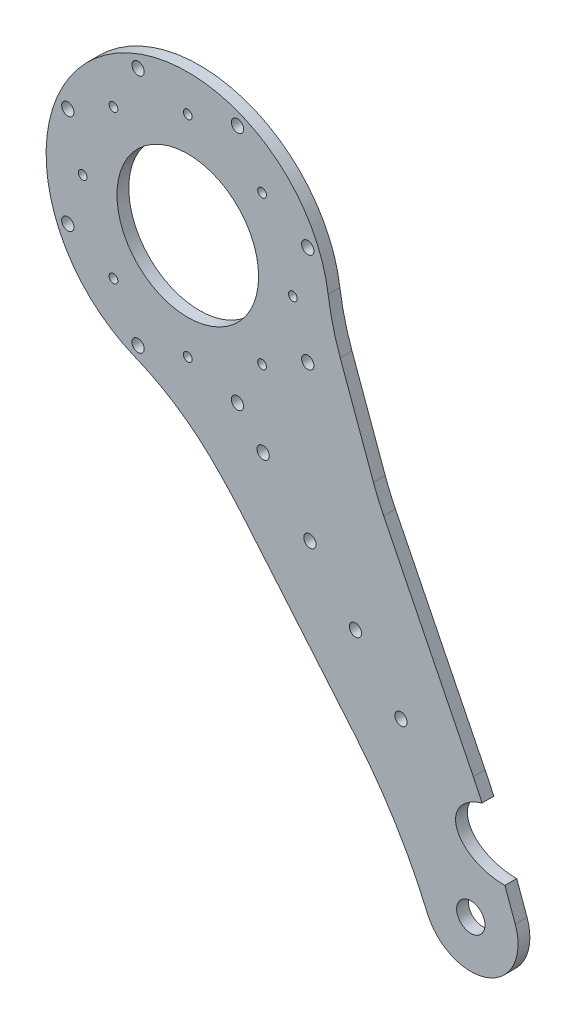
SolidWorks part; units mm, degrees
ref_plane "前视基准面" through (0, 0, 0) normal (0, 0, 1) x (1, 0, 0)
ref_plane "上视基准面" through (0, 0, 0) normal (0, 1, 0) x (1, 0, 0)
ref_plane "右视基准面" through (0, 0, 0) normal (1, 0, 0) x (0, 0, -1)
other "Configuration Table"
sketch "草图1" plane through (0, 0, 0) normal (0, 0, 1) x (1, 0, 0)
  line L0 (60, 0) -> (80.5212, -56.3816)
  line L1 (60, 0) -> (0, 0) construction
  line L2 (0, 0) -> (-56.3816, -20.5212) construction
  line L3 (-56.3816, -20.5212) -> (12.5624, -78.3721)
  line L4 (12.5624, -78.3721) -> (80.5212, -56.3816)
  line L5 (80.5212, -56.3816) -> (113.0212, -112.6732)
  line L6 (12.5624, -78.3721) -> (92.7533, -173.9399)
  line L7 (113.0212, -112.6732) -> (138.6727, -183.1502)
  line L8 (101.085, -196.831) -> (138.6727, -183.1502) construction
  line L9 (101.085, -196.831) -> (92.7533, -173.9399)
  line L10 (125.847, -147.9117) -> (80.5212, -56.3816)
  circle A0 centre (0, 0) radius 30
  circle A1 centre (0, 0) radius 60
  circle A2 centre (119.8789, -189.9906) radius 6
  circle A3 centre (119.8789, -189.9906) radius 20
  dimension "D1" = 60
  dimension "D2" = 120
  dimension "D9" = 65
  dimension "D11" = 12
  dimension "D12" = 40
  dimension "D3" = 160
  dimension "D4" = 110
  dimension "D5" = 60
  dimension "D6" = 60
  dimension "D7" = 90
  dimension "D8" = 170
  dimension "D10" = 190
  dimension "D13" = 170
  dimension "D15" = 75
  dimension "D16" = 90
extrude "凸台-拉伸1" add sketch "草图1" along normal blind 5 contours A1 L3 A0 | A1 L3 L4 L0 | A3 L7 L5 L4 L6 L9 | A3 A2
sketch "草图2" plane through (0, 0, 5) normal (0, 0, 1) x (1, 0, 0)
  line L0 (0, 60) -> (0, 0) construction
  line L1 (-60, 0) -> (60, 0) construction
  line L6 (-10.4189, -59.0885) -> (12.5624, -78.3721)
  line L7 (12.5624, -78.3721) -> (92.7533, -173.9399)
  line L8 (92.7533, -173.9399) -> (101.085, -196.831)
  line L9 (138.6727, -183.1502) -> (125.847, -147.9117)
  line L10 (125.847, -147.9117) -> (80.5212, -56.3816)
  line L11 (80.5212, -56.3816) -> (60, 0)
  line L12 (-10.4189, -59.0885) -> (12.5624, -78.3721)
  line L13 (12.5624, -78.3721) -> (92.7533, -173.9399)
  line L14 (92.7533, -173.9399) -> (101.085, -196.831)
  line L15 (138.6727, -183.1502) -> (125.847, -147.9117)
  line L16 (125.847, -147.9117) -> (80.5212, -56.3816)
  line L17 (80.5212, -56.3816) -> (60, 0)
  circle A0 centre (0, 44.5) radius 1.85
  circle A1 centre (31.4663, 31.4663) radius 1.85
  arc A2 (60, 0) -> (-10.4189, -59.0885) centre (0, 0) ccw
  arc A3 (101.085, -196.831) -> (138.6727, -183.1502) centre (119.8789, -189.9906) ccw
  arc A4 (60, 0) -> (-10.4189, -59.0885) centre (0, 0) ccw
  arc A5 (101.085, -196.831) -> (138.6727, -183.1502) centre (119.8789, -189.9906) ccw
  circle A6 centre (44.5, 0) radius 1.85
  circle A7 centre (31.4663, -31.4663) radius 1.85
  circle A8 centre (0, -44.5) radius 1.85
  circle A9 centre (-31.4663, -31.4663) radius 1.85
  circle A10 centre (-44.5, 0) radius 1.85
  circle A11 centre (-31.4663, 31.4663) radius 1.85
  circle A12 centre (42.5, 0) radius 1.6
  circle A13 centre (-42.5, 0) radius 1.85
  point P30 (0, 0)
  dimension "D2" = 3.7
  dimension "D3" = 44.5
  dimension "D5" = 3.7
  dimension "D6" = 3.2
  dimension "D7" = 42.5
  dimension "D8" = 42.5
  dimension "D1" = 0
  dimension "D4" = 8
extrude "切除-拉伸1" cut sketch "草图2" against normal blind 10 contours A0 | A1 | A6 A12 | A6 A12 | A7 | A8 | A10 A13 | A10 A13 | A11 | A9
sketch "草图3" plane through (0, 0, 5) normal (0, 0, 1) x (1, 0, 0)
  line L0 (0, 0) -> (0, 60) construction
  line L1 (0, 0) -> (31.4663, 31.4663) construction
  line L2 (0, 0) -> (22.961, 55.4328) construction
  line L6 (-10.4189, -59.0885) -> (12.5624, -78.3721)
  line L7 (12.5624, -78.3721) -> (92.7533, -173.9399)
  line L8 (92.7533, -173.9399) -> (101.085, -196.831)
  line L9 (138.6727, -183.1502) -> (125.847, -147.9117)
  line L10 (125.847, -147.9117) -> (80.5212, -56.3816)
  line L11 (80.5212, -56.3816) -> (60, 0)
  line L12 (-10.4189, -59.0885) -> (12.5624, -78.3721)
  line L13 (12.5624, -78.3721) -> (92.7533, -173.9399)
  line L14 (92.7533, -173.9399) -> (101.085, -196.831)
  line L15 (138.6727, -183.1502) -> (125.847, -147.9117)
  line L16 (125.847, -147.9117) -> (80.5212, -56.3816)
  line L17 (80.5212, -56.3816) -> (60, 0)
  circle A0 centre (21.0476, 50.8134) radius 2.6
  circle A1 centre (50.8134, 21.0476) radius 2.6
  arc A2 (60, 0) -> (-10.4189, -59.0885) centre (0, 0) ccw
  arc A3 (101.085, -196.831) -> (138.6727, -183.1502) centre (119.8789, -189.9906) ccw
  arc A4 (60, 0) -> (-10.4189, -59.0885) centre (0, 0) ccw
  arc A5 (101.085, -196.831) -> (138.6727, -183.1502) centre (119.8789, -189.9906) ccw
  circle A6 centre (50.8134, -21.0476) radius 2.6
  circle A7 centre (21.0476, -50.8134) radius 2.6
  circle A8 centre (-21.0476, -50.8134) radius 2.6
  circle A9 centre (-50.8134, -21.0476) radius 2.6
  circle A10 centre (-50.8134, 21.0476) radius 2.6
  circle A11 centre (-21.0476, 50.8134) radius 2.6
  point P33 (0, 0)
  dimension "D3" = 5.2
  dimension "D4" = 55
  dimension "D2" = 22.5
  dimension "D1" = 0
  dimension "D5" = 8
extrude "切除-拉伸2" cut sketch "草图3" against normal blind 10 contours A10 | A9 | A8 | A7 | A6 | A1 | A0 | A11
fillet "圆角1" radius 200 1 edges at (125.847, -147.9117, 2.5)
fillet "圆角2" radius 200 1 edges at (92.7533, -173.9399, 2.5)
fillet "圆角3" radius 200 1 edges at (12.5624, -78.3721, 2.5)
fillet "圆角5" radius 100 3 edges at (80.5212, -56.3816, 2.5) (60, 0, 2.5) (-10.4189, -59.0885, 2.5)
sketch "草图4" plane through (0, 0, 5) normal (0, 0, 1) x (1, 0, 0)
  line L5 (138.6727, -183.1502) -> (129.6382, -158.328)
  line L6 (120.9279, -137.9781) -> (82.9808, -61.3483)
  line L7 (78.6256, -51.1734) -> (64.5536, -12.5109)
  line L8 (23.8098, -91.7761) -> (70.6774, -147.6308)
  line L9 (42.9609, -75.7064) -> (89.8285, -131.5612)
  line L10 (138.6727, -183.1502) -> (129.6382, -158.328)
  line L11 (120.9279, -137.9781) -> (82.9808, -61.3483)
  line L12 (78.6256, -51.1734) -> (64.5536, -12.5109)
  line L13 (23.8098, -91.7761) -> (70.6774, -147.6308)
  line L15 (89.8877, -131.6317) -> (89.8877, -131.6317)
  line L16 (89.8877, -131.6317) -> (60.5772, -72.4426)
  line L17 (55.1333, -59.7239) -> (41.0613, -21.0614)
  circle A0 centre (31.9151, -63.6228) radius 2.6
  circle A1 centre (51.7254, -86.1517) radius 2.6
  circle A2 centre (63.0234, -24.2033) radius 2.6
  circle A3 centre (71.0091, -109.133) radius 2.6
  circle A4 centre (50.8134, -21.0476) radius 2.6 construction
  circle A5 centre (50.8134, -21.0476) radius 2.6
  circle A7 centre (90.2927, -132.1143) radius 2.6
  arc A8 (129.6382, -158.328) -> (120.9279, -137.9781) centre (-58.3003, -226.732) ccw
  arc A9 (78.6256, -51.1734) -> (82.9808, -61.3483) centre (172.5949, -16.9714) ccw
  arc A10 (59.4461, 8.1342) -> (64.5536, -12.5109) centre (158.5229, 21.6911) ccw
  arc A11 (59.4461, 8.1342) -> (-22.5076, -55.6184) centre (0, 0) ccw
  arc A12 (9.3586, -76.2979) -> (-22.5076, -55.6184) centre (-60.0203, -148.3158) ccw
  arc A13 (23.8098, -91.7761) -> (9.3586, -76.2979) centre (-129.3991, -220.3337) ccw
  arc A14 (101.4779, -197.8267) -> (70.6774, -147.6308) centre (-82.5315, -276.1884) ccw
  arc A15 (101.4779, -197.8267) -> (138.6727, -183.1502) centre (119.8789, -189.9906) ccw
  arc A16 (129.6382, -158.328) -> (120.9279, -137.9781) centre (-58.3003, -226.732) ccw
  arc A17 (78.6256, -51.1734) -> (82.9808, -61.3483) centre (172.5949, -16.9714) ccw
  arc A18 (59.4461, 8.1342) -> (64.5536, -12.5109) centre (158.5229, 21.6911) ccw
  arc A19 (59.4461, 8.1342) -> (-22.5076, -55.6184) centre (0, 0) ccw
  arc A20 (9.3586, -76.2979) -> (-22.5076, -55.6184) centre (-60.0203, -148.3158) ccw
  arc A21 (23.8098, -91.7761) -> (9.3586, -76.2979) centre (-129.3991, -220.3337) ccw
  arc A22 (101.4779, -197.8267) -> (70.6774, -147.6308) centre (-82.5315, -276.1884) ccw
  arc A23 (101.4779, -197.8267) -> (138.6727, -183.1502) centre (119.8789, -189.9906) ccw
  arc A38 (89.8877, -131.6317) -> (89.8285, -131.5612) centre (-82.5315, -276.1884) ccw
  arc A39 (89.8877, -131.6317) -> (89.8877, -131.6317) centre (89.8877, -131.6317) ccw
  arc A40 (89.8877, -131.6317) -> (89.8877, -131.6317) centre (89.8877, -131.6317) ccw
  arc A41 (55.1333, -59.7239) -> (60.5772, -72.4426) centre (172.5949, -16.9714) ccw
  arc A42 (34.6769, 4.7449) -> (41.0613, -21.0614) centre (158.5229, 21.6911) ccw
  arc A43 (34.6769, 4.7449) -> (-13.1294, -32.4441) centre (0, 0) ccw
  arc A44 (26.7033, -58.2934) -> (-13.1294, -32.4441) centre (-60.0203, -148.3158) ccw
  arc A45 (42.9609, -75.7064) -> (26.7033, -58.2934) centre (-129.3991, -220.3337) ccw
  dimension "D2" = 5.2
  dimension "D3" = 5.2
  dimension "D4" = 5.2
  dimension "D5" = 5.2
  dimension "D7" = 30
  dimension "D8" = 30
  dimension "D9" = 30
  dimension "D10" = 65
  dimension "D13" = 5.2
  dimension "D1" = 0
  dimension "D6" = 25
extrude "切除-拉伸3" cut sketch "草图4" against normal blind 10
sketch "草图5" plane through (0, 0, 5) normal (0, 0, 1) x (1, 0, 0)
  ellipse E0 centre (133.0183, -157.9676) end of major axis (152.6156, -159.0188) minor radius 13.1666
extrude "切除-拉伸4" cut sketch "草图5" against normal blind 10 contours E0
sketch "草图6" plane through (0, 0, 5) normal (0, 0, 1) x (1, 0, 0)
  line L6 (-10.4189, -59.0885) -> (12.5624, -78.3721)
  line L7 (12.5624, -78.3721) -> (92.7533, -173.9399)
  line L8 (92.7533, -173.9399) -> (101.085, -196.831)
  line L9 (138.6727, -183.1502) -> (125.847, -147.9117)
  line L10 (125.847, -147.9117) -> (80.5212, -56.3816)
  line L11 (80.5212, -56.3816) -> (60, 0)
  line L12 (-10.4189, -59.0885) -> (12.5624, -78.3721)
  line L13 (12.5624, -78.3721) -> (92.7533, -173.9399)
  line L14 (92.7533, -173.9399) -> (101.085, -196.831)
  line L15 (138.6727, -183.1502) -> (125.847, -147.9117)
  line L16 (125.847, -147.9117) -> (80.5212, -56.3816)
  line L17 (80.5212, -56.3816) -> (60, 0)
  circle A1 centre (42.5, 0) radius 1.6
  circle A2 centre (42.5, 0) radius 1.6
  circle A3 centre (0, 44.5) radius 1.85
  circle A4 centre (0, 44.5) radius 1.85
  circle A5 centre (-31.4663, 31.4663) radius 1.85
  arc A6 (101.085, -196.831) -> (138.6727, -183.1502) centre (119.8789, -189.9906) ccw
  arc A7 (60, 0) -> (-10.4189, -59.0885) centre (0, 0) ccw
  arc A8 (101.085, -196.831) -> (138.6727, -183.1502) centre (119.8789, -189.9906) ccw
  arc A9 (60, 0) -> (-10.4189, -59.0885) centre (0, 0) ccw
  circle A10 centre (-31.4663, 31.4663) radius 1.85
  circle A11 centre (-44.5, 0) radius 1.85
  circle A12 centre (-44.5, 0) radius 1.85
  circle A13 centre (-31.4663, -31.4663) radius 1.85
  circle A14 centre (-31.4663, -31.4663) radius 1.85
  circle A15 centre (0, -44.5) radius 1.85
  circle A16 centre (0, -44.5) radius 1.85
  circle A17 centre (31.4663, -31.4663) radius 1.85
  circle A18 centre (31.4663, -31.4663) radius 1.85
  circle A19 centre (44.5, 0) radius 1.85
  circle A20 centre (44.5, 0) radius 1.85
  circle A21 centre (31.4663, 31.4663) radius 1.85
  circle A22 centre (31.4663, 31.4663) radius 1.85
  circle A23 centre (-42.5, 0) radius 1.85
  circle A24 centre (-42.5, 0) radius 1.85
  circle M46 centre (42.5, 0) radius 1.6
  circle M49 centre (-42.5, 0) radius 1.85
  dimension "D1" = 0
  dimension "D2" = 0
  dimension "D3" = 0
  dimension "D4" = 0
  dimension "D5" = 0
  dimension "D6" = 0
  dimension "D7" = 0
  dimension "D8" = 0
  dimension "D9" = 0
  dimension "D10" = 0
  dimension "D11" = 0
extrude "凸台-拉伸2" add sketch "草图6" against normal through all contours A12 M49 | A12 M49 | A2 A20 | A20 M46
sketch "草图7" plane through (0, 0, 5) normal (0, 0, 1) x (1, 0, 0)
  line L4 (120.9279, -137.9781) -> (82.9808, -61.3483)
  line L5 (78.6256, -51.1734) -> (64.5536, -12.5109)
  line L6 (23.8098, -91.7761) -> (70.6774, -147.6308)
  line L7 (138.6727, -183.1502) -> (134.3065, -171.1541)
  line L8 (120.9279, -137.9781) -> (82.9808, -61.3483)
  line L9 (78.6256, -51.1734) -> (64.5536, -12.5109)
  line L10 (23.8098, -91.7761) -> (70.6774, -147.6308)
  line L11 (138.6727, -183.1502) -> (134.3065, -171.1541)
  line L14 (-10.4189, -59.0885) -> (12.5624, -78.3721)
  line L15 (12.5624, -78.3721) -> (92.7533, -173.9399)
  line L16 (92.7533, -173.9399) -> (101.085, -196.831)
  line L17 (138.6727, -183.1502) -> (125.847, -147.9117)
  line L18 (125.847, -147.9117) -> (80.5212, -56.3816)
  line L19 (80.5212, -56.3816) -> (60, 0)
  line L20 (-10.4189, -59.0885) -> (12.5624, -78.3721)
  line L21 (12.5624, -78.3721) -> (92.7533, -173.9399)
  line L22 (92.7533, -173.9399) -> (101.085, -196.831)
  line L23 (138.6727, -183.1502) -> (125.847, -147.9117)
  line L24 (125.847, -147.9117) -> (80.5212, -56.3816)
  line L25 (80.5212, -56.3816) -> (60, 0)
  circle A1 centre (42.5, 0) radius 1.6
  circle A2 centre (42.5, 0) radius 1.6
  circle A3 centre (0, 44.5) radius 1.85
  circle A4 centre (0, 44.5) radius 1.85
  circle A5 centre (-31.4663, 31.4663) radius 1.85
  arc A6 (101.085, -196.831) -> (138.6727, -183.1502) centre (119.8789, -189.9906) ccw
  arc A7 (60, 0) -> (-10.4189, -59.0885) centre (0, 0) ccw
  arc A8 (124.6011, -145.8182) -> (120.9279, -137.9781) centre (-58.3003, -226.732) ccw
  arc A9 (78.6256, -51.1734) -> (82.9808, -61.3483) centre (172.5949, -16.9714) ccw
  arc A10 (59.4461, 8.1342) -> (64.5536, -12.5109) centre (158.5229, 21.6911) ccw
  arc A11 (59.4461, 8.1342) -> (-22.5076, -55.6184) centre (0, 0) ccw
  arc A12 (9.3586, -76.2979) -> (-22.5076, -55.6184) centre (-60.0203, -148.3158) ccw
  arc A13 (23.8098, -91.7761) -> (9.3586, -76.2979) centre (-129.3991, -220.3337) ccw
  arc A14 (101.4779, -197.8267) -> (70.6774, -147.6308) centre (-82.5315, -276.1884) ccw
  arc A15 (101.4779, -197.8267) -> (138.6727, -183.1502) centre (119.8789, -189.9906) ccw
  arc A16 (124.6011, -145.8182) -> (120.9279, -137.9781) centre (-58.3003, -226.732) ccw
  arc A17 (78.6256, -51.1734) -> (82.9808, -61.3483) centre (172.5949, -16.9714) ccw
  arc A18 (59.4461, 8.1342) -> (64.5536, -12.5109) centre (158.5229, 21.6911) ccw
  arc A19 (59.4461, 8.1342) -> (-22.5076, -55.6184) centre (0, 0) ccw
  arc A20 (9.3586, -76.2979) -> (-22.5076, -55.6184) centre (-60.0203, -148.3158) ccw
  arc A21 (23.8098, -91.7761) -> (9.3586, -76.2979) centre (-129.3991, -220.3337) ccw
  arc A22 (101.4779, -197.8267) -> (70.6774, -147.6308) centre (-82.5315, -276.1884) ccw
  arc A23 (101.4779, -197.8267) -> (138.6727, -183.1502) centre (119.8789, -189.9906) ccw
  arc A24 (101.085, -196.831) -> (138.6727, -183.1502) centre (119.8789, -189.9906) ccw
  arc A25 (60, 0) -> (-10.4189, -59.0885) centre (0, 0) ccw
  circle A26 centre (-31.4663, 31.4663) radius 1.85
  circle A27 centre (-44.5, 0) radius 1.85
  circle A28 centre (-44.5, 0) radius 1.85
  circle A29 centre (-31.4663, -31.4663) radius 1.85
  circle A30 centre (-31.4663, -31.4663) radius 1.85
  circle A31 centre (0, -44.5) radius 1.85
  circle A32 centre (0, -44.5) radius 1.85
  circle A33 centre (31.4663, -31.4663) radius 1.85
  circle A34 centre (31.4663, -31.4663) radius 1.85
  circle A35 centre (44.5, 0) radius 1.85
  circle A36 centre (44.5, 0) radius 1.85
  circle A37 centre (31.4663, 31.4663) radius 1.85
  circle A38 centre (31.4663, 31.4663) radius 1.85
  circle A39 centre (-42.5, 0) radius 1.85
  circle A40 centre (-42.5, 0) radius 1.85
  ellipse E1 centre (133.0183, -157.9676) end of major axis (152.6156, -159.0188) minor radius 13.1666 (124.6011, -145.8182) -> (134.3065, -171.1541) ccw
  ellipse E2 centre (133.0183, -157.9676) end of major axis (152.6156, -159.0188) minor radius 13.1666 (124.6011, -145.8182) -> (134.3065, -171.1541) ccw
  dimension "D1" = 0
  dimension "D2" = 0
  dimension "D3" = 0
  dimension "D4" = 0
  dimension "D5" = 0
  dimension "D6" = 0
  dimension "D7" = 0
  dimension "D8" = 0
  dimension "D9" = 0
  dimension "D10" = 0
  dimension "D11" = 0
  dimension "D12" = 0
extrude "切除-拉伸5" cut sketch "草图7" against normal blind 10 contours A40 A28 | A28 A40 | A2 A36 | A2 A36
sketch "草图8" plane through (0, 0, 5) normal (0, 0, 1) x (1, 0, 0)
  line L4 (120.9279, -137.9781) -> (82.9808, -61.3483)
  line L5 (78.6256, -51.1734) -> (64.5536, -12.5109)
  line L6 (23.8098, -91.7761) -> (70.6774, -147.6308)
  line L7 (138.6727, -183.1502) -> (134.3065, -171.1541)
  line L8 (120.9279, -137.9781) -> (82.9808, -61.3483)
  line L9 (78.6256, -51.1734) -> (64.5536, -12.5109)
  line L10 (23.8098, -91.7761) -> (70.6774, -147.6308)
  line L11 (138.6727, -183.1502) -> (134.3065, -171.1541)
  circle A1 centre (-44.5, 0) radius 1.85
  circle A2 centre (-44.5, 0) radius 1.85
  circle A3 centre (44.5, 0) radius 1.85
  circle A4 centre (44.5, 0) radius 1.85
  circle A5 centre (-31.4663, -31.4663) radius 1.85
  circle A6 centre (-31.4663, -31.4663) radius 1.85
  circle A7 centre (0, 0) radius 30
  circle A8 centre (0, 0) radius 30
  circle A9 centre (119.8789, -189.9906) radius 6
  circle A10 centre (119.8789, -189.9906) radius 6
  circle A11 centre (-31.4663, 31.4663) radius 1.85
  circle A12 centre (-31.4663, 31.4663) radius 1.85
  circle A13 centre (0, -44.5) radius 1.85
  circle A14 centre (0, -44.5) radius 1.85
  circle A15 centre (31.4663, -31.4663) radius 1.85
  circle A16 centre (31.4663, -31.4663) radius 1.85
  circle A17 centre (31.4663, 31.4663) radius 1.85
  circle A18 centre (31.4663, 31.4663) radius 1.85
  circle A19 centre (0, 44.5) radius 1.85
  circle A20 centre (0, 44.5) radius 1.85
  circle A21 centre (-50.8134, 21.0476) radius 2.6
  circle A22 centre (-50.8134, 21.0476) radius 2.6
  circle A23 centre (-21.0476, 50.8134) radius 2.6
  circle A24 centre (-21.0476, 50.8134) radius 2.6
  circle A25 centre (21.0476, 50.8134) radius 2.6
  circle A26 centre (21.0476, 50.8134) radius 2.6
  circle A27 centre (50.8134, 21.0476) radius 2.6
  circle A28 centre (50.8134, 21.0476) radius 2.6
  circle A29 centre (50.8134, -21.0476) radius 2.6
  circle A30 centre (50.8134, -21.0476) radius 2.6
  circle A31 centre (21.0476, -50.8134) radius 2.6
  circle A32 centre (21.0476, -50.8134) radius 2.6
  circle A33 centre (-21.0476, -50.8134) radius 2.6
  circle A34 centre (-21.0476, -50.8134) radius 2.6
  circle A35 centre (-50.8134, -21.0476) radius 2.6
  circle A36 centre (-50.8134, -21.0476) radius 2.6
  circle A37 centre (71.0091, -109.133) radius 2.6
  circle A38 centre (71.0091, -109.133) radius 2.6
  circle A39 centre (31.9151, -63.6228) radius 2.6
  circle A40 centre (31.9151, -63.6228) radius 2.6
  circle A41 centre (51.7254, -86.1517) radius 2.6
  circle A42 centre (51.7254, -86.1517) radius 2.6
  circle A43 centre (90.2927, -132.1143) radius 2.6
  circle A44 centre (90.2927, -132.1143) radius 2.6
  arc A52 (124.6011, -145.8182) -> (120.9279, -137.9781) centre (-58.3003, -226.732) ccw
  arc A53 (78.6256, -51.1734) -> (82.9808, -61.3483) centre (172.5949, -16.9714) ccw
  arc A54 (59.4461, 8.1342) -> (64.5536, -12.5109) centre (158.5229, 21.6911) ccw
  arc A55 (59.4461, 8.1342) -> (-22.5076, -55.6184) centre (0, 0) ccw
  arc A56 (9.3586, -76.2979) -> (-22.5076, -55.6184) centre (-60.0203, -148.3158) ccw
  arc A57 (23.8098, -91.7761) -> (9.3586, -76.2979) centre (-129.3991, -220.3337) ccw
  arc A58 (101.4779, -197.8267) -> (70.6774, -147.6308) centre (-82.5315, -276.1884) ccw
  arc A59 (101.4779, -197.8267) -> (138.6727, -183.1502) centre (119.8789, -189.9906) ccw
  arc A60 (124.6011, -145.8182) -> (120.9279, -137.9781) centre (-58.3003, -226.732) ccw
  arc A61 (78.6256, -51.1734) -> (82.9808, -61.3483) centre (172.5949, -16.9714) ccw
  arc A62 (59.4461, 8.1342) -> (64.5536, -12.5109) centre (158.5229, 21.6911) ccw
  arc A63 (59.4461, 8.1342) -> (-22.5076, -55.6184) centre (0, 0) ccw
  arc A64 (9.3586, -76.2979) -> (-22.5076, -55.6184) centre (-60.0203, -148.3158) ccw
  arc A65 (23.8098, -91.7761) -> (9.3586, -76.2979) centre (-129.3991, -220.3337) ccw
  arc A66 (101.4779, -197.8267) -> (70.6774, -147.6308) centre (-82.5315, -276.1884) ccw
  arc A67 (101.4779, -197.8267) -> (138.6727, -183.1502) centre (119.8789, -189.9906) ccw
  ellipse E1 centre (133.0183, -157.9676) end of major axis (152.6156, -159.0188) minor radius 13.1666 (124.6011, -145.8182) -> (134.3065, -171.1541) ccw
  ellipse E2 centre (133.0183, -157.9676) end of major axis (152.6156, -159.0188) minor radius 13.1666 (124.6011, -145.8182) -> (134.3065, -171.1541) ccw
  dimension "D1" = 0
  dimension "D2" = 0
  dimension "D3" = 0
  dimension "D4" = 0
  dimension "D5" = 0
  dimension "D6" = 0
  dimension "D7" = 0
  dimension "D8" = 0
  dimension "D9" = 0
  dimension "D10" = 0
  dimension "D11" = 0
  dimension "D12" = 0
  dimension "D13" = 0
  dimension "D14" = 0
  dimension "D15" = 0
  dimension "D16" = 0
  dimension "D17" = 0
  dimension "D18" = 0
  dimension "D19" = 0
  dimension "D20" = 0
  dimension "D21" = 0
  dimension "D22" = 0
  dimension "D23" = 0
